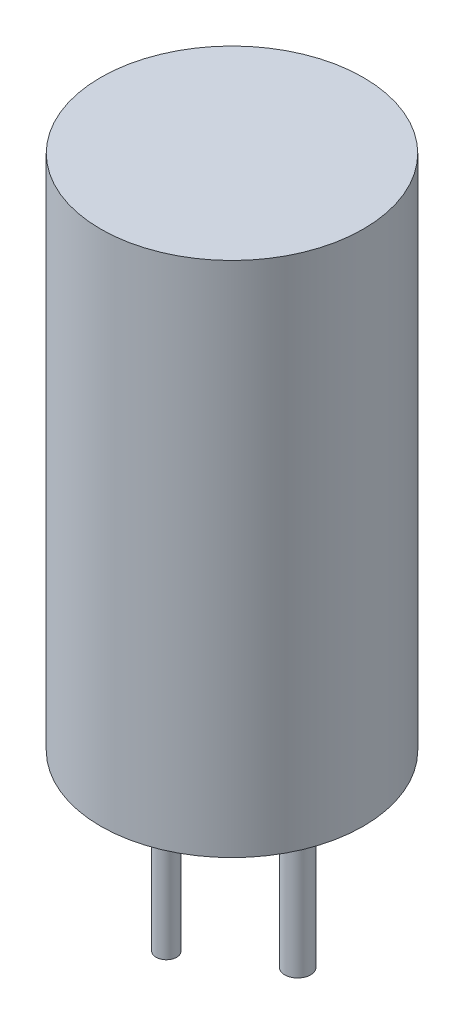
SolidWorks part; units mm, degrees
ref_plane "前视基准面" through (0, 0, 0) normal (0, 0, 1) x (1, 0, 0)
ref_plane "上视基准面" through (0, 0, 0) normal (0, 1, 0) x (1, 0, 0)
ref_plane "右视基准面" through (0, 0, 0) normal (1, 0, 0) x (0, 0, -1)
sketch "草图1" plane through (0, 0, 0) normal (0, 1, 0) x (1, 0, 0)
  circle A0 centre (0, 0) radius 5.08
  dimension "D1" = 10.16
extrude "拉伸1" add sketch "草图1" along normal blind 20
sketch "草图2" plane through (0, 0, 0) normal (0, -1, 0) x (1, 0, 0)
  line L0 (4.8023, 0) -> (-11.2367, 0) construction
  circle A0 centre (-2.54, 0) radius 0.4
  dimension "D2" = 0.8
  dimension "D1" = 2.54
extrude "拉伸2" add sketch "草图2" along normal blind 8
sketch "草图3" plane through (0, 0, 0) normal (0, -1, 0) x (1, 0, 0)
  line L0 (7.1249, 0) -> (-2.8562, 0) construction
  circle A0 centre (2.54, 0) radius 0.5
  dimension "D1" = 1
  dimension "D2" = 2.54
extrude "拉伸3" add sketch "草图3" along normal blind 6
